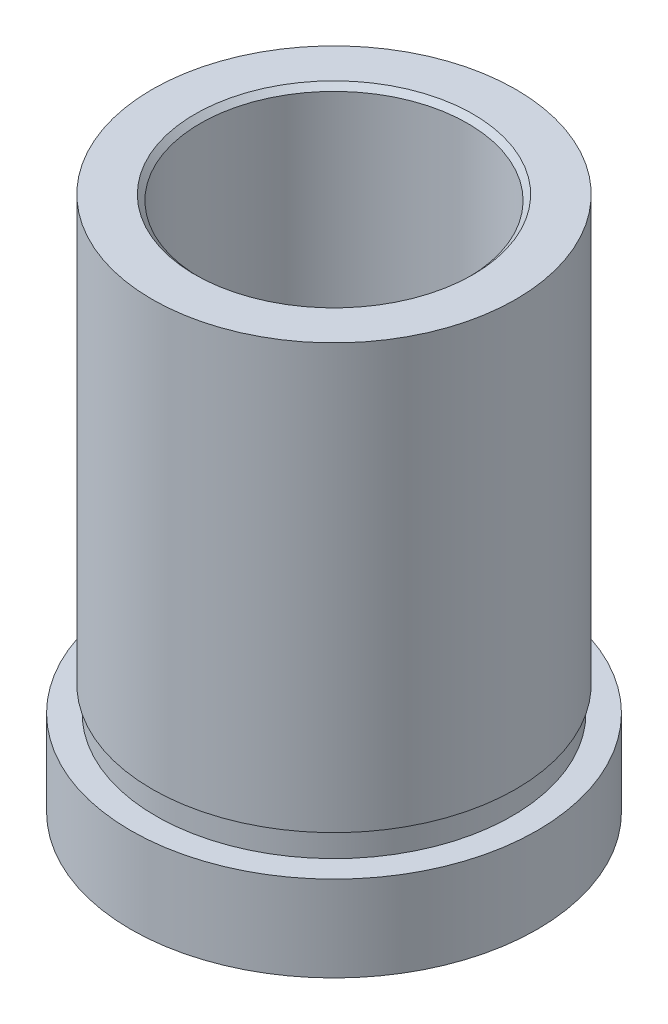
SolidWorks part; units mm, degrees
ref_plane "FP" through (0, 0, 0) normal (0, 0, 1) x (1, 0, 0)
ref_plane "TP" through (0, 0, 0) normal (0, 1, 0) x (1, 0, 0)
ref_plane "RP" through (0, 0, 0) normal (1, 0, 0) x (0, 0, -1)
sketch "Sketch1" plane through (0, 0, 0) normal (0, 0, 1) x (1, 0, 0)
  line L0 (0, 0) -> (19, 0)
  line L1 (19, 0) -> (19, 8)
  line L2 (19, 8) -> (16.65, 8)
  line L3 (16.65, 8) -> (16.65, 10.35)
  line L4 (16.65, 10.35) -> (17, 10.35)
  line L5 (17, 10.35) -> (17, 50)
  line L6 (17, 50) -> (0, 50)
  line L7 (0, 50) -> (0, 0)
  point P3 (17, 15.7239)
  point P9 (17, 13.3813)
  dimension "D1" = 19
  dimension "D2" = 17
  dimension "D3" = 50
  dimension "D4" = 8
  dimension "D5" = 2.35
revolve "Revolve1" add sketch "Sketch1" angle 360 about L7
sketch "Sketch2" plane through (0, 0, 0) normal (0, -1, 0) x (1, 0, 0)
  circle A0 centre (0, 0) radius 12.5
  dimension "D1" = 25
extrude "Cut-Extrude1" cut sketch "Sketch2" against normal through all both and the other way through all
sketch "Sketch4" plane through (0, 0, 0) normal (0, -1, 0) x (1, 0, 0)
  circle A0 centre (0, 0) radius 12.6
  dimension "D1" = 25.2
extrude "Cut-Extrude2" cut sketch "Sketch4" against normal blind 16
chamfer "Chamfer4" distance 0.5 angle 45 1 edges at (12.6, 0, 0)
chamfer "Chamfer5" distance 0.5 angle 45 1 edges at (12.5, 50, 0)
equation "\"D1\"= 25"
equation "\"D2\"= 34"
equation "\"D3\"= 38"
equation "\"K\"= 8"
equation "\"L\"= 50"
equation "\"D1@Sketch1\"=\"D3\"/2"
equation "\"D2@Sketch1\"=\"D2\"/2"
equation "\"D3@Sketch1\"=\"L\""
equation "\"D4@Sketch1\"=\"K\""
equation "\"D1@Sketch2\"=\"D1\""
equation "\"D1@Sketch4\"=\"D1\"+0.2"
equation "\"D1@Cut-Extrude2\"=\"K\"*2"
equation "\"D1@Chamfer5\"=0.5"
